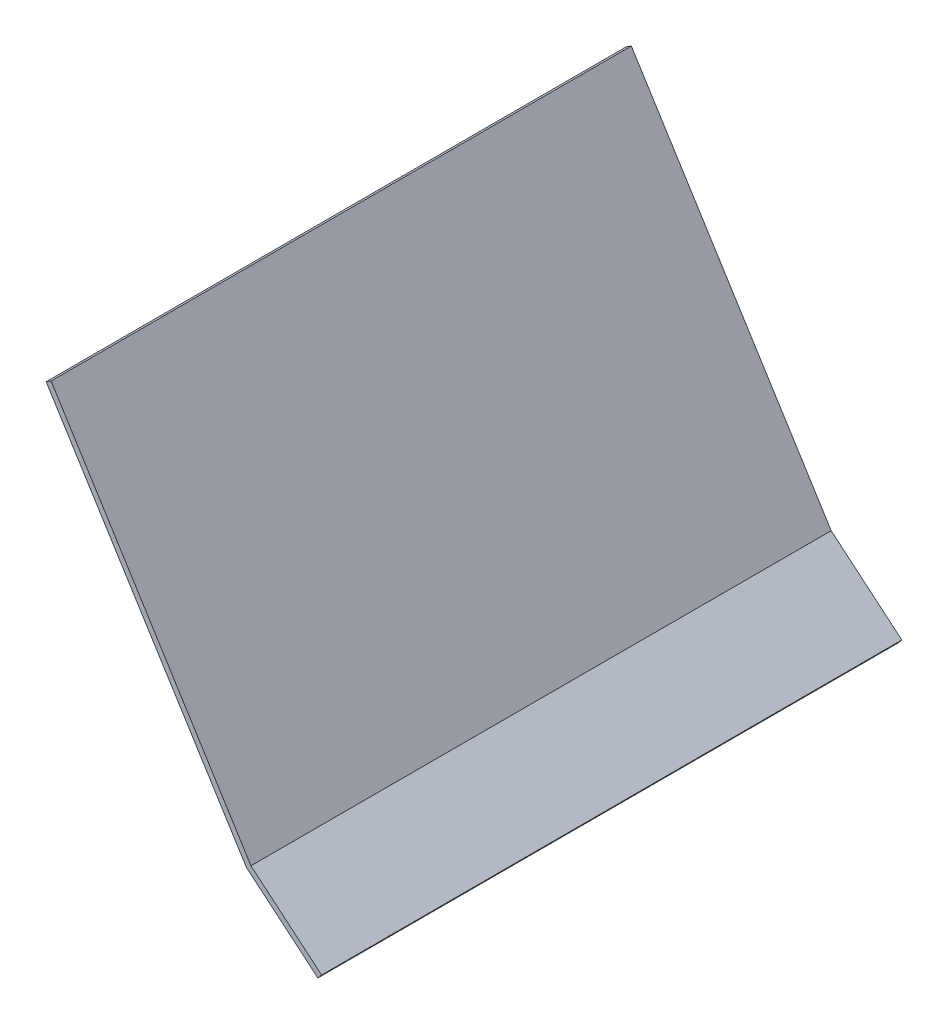
SolidWorks part; units mm, degrees
ref_plane "Plano frontal" through (0, 0, 0) normal (0, 0, 1) x (1, 0, 0)
ref_plane "Plano superior" through (0, 0, 0) normal (0, 1, 0) x (1, 0, 0)
ref_plane "Plano direito" through (0, 0, 0) normal (1, 0, 0) x (0, 0, -1)
sketch "Esboço1" plane through (0, 0, 0) normal (0, 0, 1) x (1, 0, 0)
  line L0 (-9.8284, 4.5709) -> (-22.1268, 14.8905)
  line L1 (-22.1268, 14.8905) -> (-31.5683, 30)
  line L2 (-31.5683, 30) -> (-56.6555, 70.148)
  line L3 (-9.1856, 5.337) -> (-21.3627, 15.5548)
  line L4 (-21.3627, 15.5548) -> (-30.7202, 30.5299)
  line L5 (-30.7202, 30.5299) -> (-55.8075, 70.6779)
  line L6 (-56.6555, 70.148) -> (-55.8075, 70.6779)
  line L7 (-9.8284, 4.5709) -> (-9.1856, 5.337)
  dimension "D2" = 65
  dimension "D1" = 1
extrude "Ressalto-extrusão1" add sketch "Esboço1" against normal blind 100
